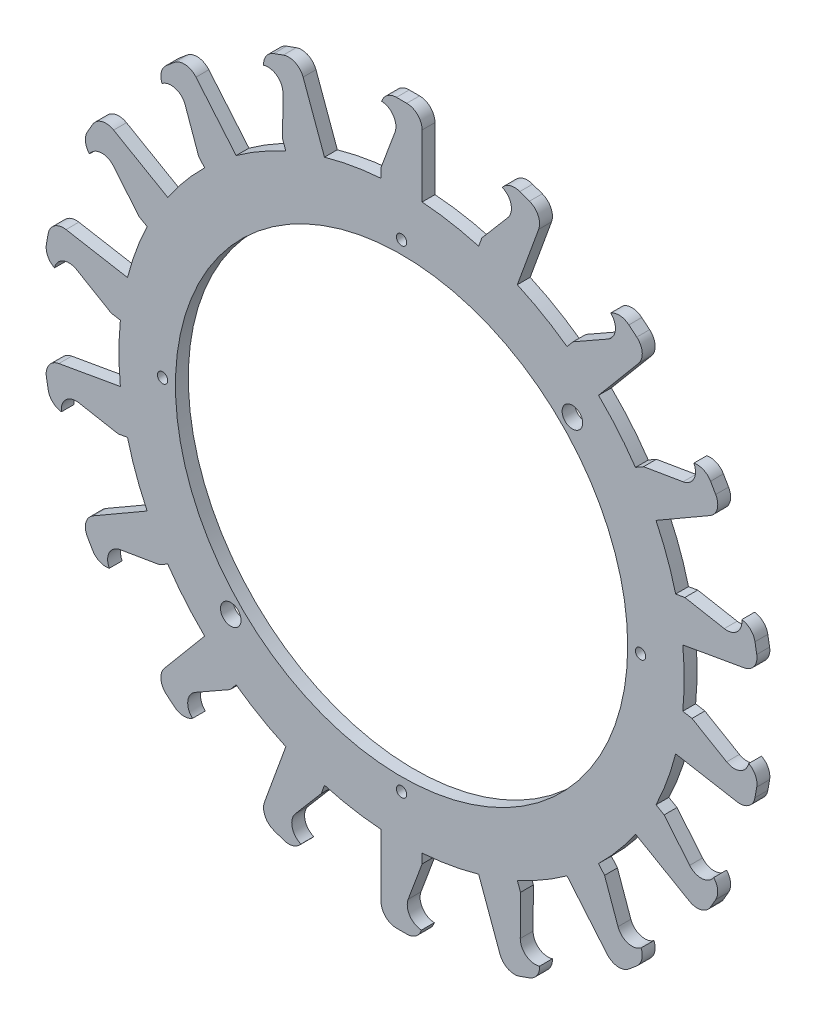
SolidWorks part; units mm, degrees
ref_plane "Front Plane" through (0, 0, 0) normal (0, 0, 1) x (1, 0, 0)
ref_plane "Top Plane" through (0, 0, 0) normal (0, 1, 0) x (1, 0, 0)
ref_plane "Right Plane" through (0, 0, 0) normal (1, 0, 0) x (0, 0, -1)
sketch "Sketch1" plane through (0, 0, 0) normal (0, 0, 1) x (1, 0, 0)
  line L0 (-78.3987, -3.3654) -> (61.3013, -3.3654) construction
  line L1 (-5.8227, 60.5836) -> (-5.8227, 59.1774)
  line L2 (-57.9401, 46.026) -> (40.8427, -52.7569) construction
  line L3 (40.8427, 46.026) -> (-57.9401, -52.7569) construction
  line L4 (-13.4427, 60.5073) -> (-13.4427, 59.1774)
  line L5 (-13.4427, 59.1774) -> (-5.8227, 59.1774)
  line L12 (2.7798, 58.212) -> (10.1401, 56.2398)
  line L13 (10.5041, 57.5981) -> (10.1401, 56.2398)
  line L14 (3.124, 59.4967) -> (2.7798, 58.212)
  line L18 (18.1997, 53.0809) -> (24.7988, 49.2709)
  line L19 (25.5019, 50.4887) -> (24.7988, 49.2709)
  line L20 (18.8647, 54.2327) -> (18.1997, 53.0809)
  line L24 (31.7661, 44.1336) -> (37.1543, 38.7454)
  line L25 (38.1486, 39.7398) -> (37.1543, 38.7454)
  line L26 (32.7065, 45.074) -> (31.7661, 44.1336)
  line L30 (42.5546, 31.9799) -> (46.3646, 25.3808)
  line L31 (47.5824, 26.0839) -> (46.3646, 25.3808)
  line L32 (43.7063, 32.6449) -> (42.5546, 31.9799)
  line L36 (49.8298, 17.4482) -> (51.802, 10.0878)
  line L37 (53.1603, 10.4518) -> (51.802, 10.0878)
  line L38 (51.1145, 17.7924) -> (49.8298, 17.4482)
  line L42 (53.0961, 1.5286) -> (53.0961, -6.0914)
  line L43 (54.5023, -6.0914) -> (53.0961, -6.0914)
  line L44 (54.426, 1.5286) -> (53.0961, 1.5286)
  line L48 (52.1307, -14.6939) -> (50.1585, -22.0543)
  line L49 (51.5168, -22.4183) -> (50.1585, -22.0543)
  line L50 (53.4154, -15.0382) -> (52.1307, -14.6939)
  line L54 (46.9996, -30.1138) -> (43.1896, -36.713)
  line L55 (44.4074, -37.4161) -> (43.1896, -36.713)
  line L56 (48.1513, -30.7788) -> (46.9996, -30.1138)
  line L60 (38.0523, -43.6803) -> (32.6641, -49.0684)
  line L61 (33.6585, -50.0628) -> (32.6641, -49.0684)
  line L62 (38.9927, -44.6207) -> (38.0523, -43.6803)
  line L66 (25.8986, -54.4687) -> (19.2995, -58.2787)
  line L67 (20.0026, -59.4965) -> (19.2995, -58.2787)
  line L68 (26.5636, -55.6205) -> (25.8986, -54.4687)
  line L72 (11.3669, -61.744) -> (4.0065, -63.7162)
  line L73 (4.3705, -65.0745) -> (4.0065, -63.7162)
  line L74 (11.7111, -63.0286) -> (11.3669, -61.744)
  line L78 (-4.5527, -65.0102) -> (-12.1727, -65.0102)
  line L79 (-12.1727, -66.4164) -> (-12.1727, -65.0102)
  line L80 (-4.5527, -66.3402) -> (-4.5527, -65.0102)
  line L84 (-20.7752, -64.0449) -> (-28.1356, -62.0727)
  line L85 (-28.4996, -63.431) -> (-28.1356, -62.0727)
  line L86 (-21.1195, -65.3295) -> (-20.7752, -64.0449)
  line L90 (-36.1951, -58.9137) -> (-42.7943, -55.1037)
  line L91 (-43.4974, -56.3215) -> (-42.7943, -55.1037)
  line L92 (-36.8601, -60.0655) -> (-36.1951, -58.9137)
  line L96 (-49.7616, -49.9665) -> (-55.1497, -44.5783)
  line L97 (-56.1441, -45.5726) -> (-55.1497, -44.5783)
  line L98 (-50.702, -50.9069) -> (-49.7616, -49.9665)
  line L102 (-60.55, -37.8128) -> (-64.36, -31.2137)
  line L103 (-65.5778, -31.9168) -> (-64.36, -31.2137)
  line L104 (-61.7018, -38.4778) -> (-60.55, -37.8128)
  line L109 (-71.1558, -16.2846) -> (-69.7975, -15.9207)
  line L110 (-69.1099, -23.6252) -> (-67.8253, -23.281)
  line L114 (-71.0915, -7.3614) -> (-71.0915, 0.2586)
  line L115 (-72.4977, 0.2586) -> (-71.0915, 0.2586)
  line L116 (-72.4215, -7.3614) -> (-71.0915, -7.3614)
  line L120 (-70.1262, 8.8611) -> (-68.154, 16.2214)
  line L121 (-69.5123, 16.5854) -> (-68.154, 16.2214)
  line L122 (-71.4108, 9.2053) -> (-70.1262, 8.8611)
  line L126 (-64.995, 24.281) -> (-61.185, 30.8801)
  line L127 (-62.4028, 31.5832) -> (-61.185, 30.8801)
  line L128 (-66.1468, 24.946) -> (-64.995, 24.281)
  line L132 (-56.0478, 37.8474) -> (-50.6596, 43.2356)
  line L133 (-51.6539, 44.2299) -> (-50.6596, 43.2356)
  line L134 (-56.9882, 38.7878) -> (-56.0478, 37.8474)
  line L138 (-43.8941, 48.6359) -> (-37.295, 52.4459)
  line L139 (-37.9981, 53.6637) -> (-37.295, 52.4459)
  line L140 (-44.5591, 49.7877) -> (-43.8941, 48.6359)
  line L144 (-29.3623, 55.9111) -> (-22.002, 57.8833)
  line L145 (-22.3659, 59.2416) -> (-22.002, 57.8833)
  line L146 (-29.7065, 57.1958) -> (-29.3623, 55.9111)
  line L147 (-8.9977, -2.9164) -> (-5.8227, 59.1774) construction
  line L148 (-8.9977, -2.9164) -> (10.1401, 56.2398) construction
  line L170 (-67.8253, -23.281) -> (-69.7975, -15.9207) [skipped]
  circle A0 centre (-8.5487, -3.3654) radius 55.88
  circle A1 centre (-8.5487, -3.3654) radius 69.85
  dimension "D1" = 111.76
  dimension "D2" = 139.7
  dimension "D4" = 7.62
  dimension "D5" = 24
  dimension "D6" = 15
extrude "Boss-Extrude1" add sketch "Sketch1" along normal blind 3.175
sketch "Sketch2" plane through (0, 0, 3.175) normal (0, 0, -1) x (-1, 0, 0)
  line L0 (8.5487, 66.4846) -> (8.5487, -73.2154) construction
  line L1 (8.5487, 62.6746) -> (13.6287, 62.6746)
  line L2 (8.5487, 62.6746) -> (3.4687, 62.6746)
  line L3 (3.4687, 62.6746) -> (3.4687, 85.5346)
  line L4 (3.4687, 85.5346) -> (13.6287, 85.5346)
  line L5 (13.6287, 85.5346) -> (13.6287, 62.6746)
  line L6 (8.5487, -3.3654) -> (-61.3013, -3.3654) construction
  line L7 (34.1807, 81.9107) -> (43.7279, 78.4358)
  line L8 (43.7279, 78.4358) -> (35.9094, 56.9544)
  line L9 (26.3621, 60.4293) -> (34.1807, 81.9107)
  line L10 (31.1357, 58.6919) -> (26.3621, 60.4293)
  line L11 (31.1357, 58.6919) -> (35.9094, 56.9544)
  line L12 (61.801, 68.0013) -> (69.584, 61.4705)
  line L13 (69.584, 61.4705) -> (54.8899, 43.9588)
  line L14 (47.1069, 50.4895) -> (61.801, 68.0013)
  line L15 (50.9984, 47.2241) -> (47.1069, 50.4895)
  line L16 (50.9984, 47.2241) -> (54.8899, 43.9588)
  line L17 (82.9984, 45.484) -> (88.0784, 36.6851)
  line L18 (88.0784, 36.6851) -> (68.281, 25.2551)
  line L19 (63.201, 34.054) -> (82.9984, 45.484)
  line L20 (65.741, 29.6546) -> (63.201, 34.054)
  line L21 (65.741, 29.6546) -> (68.281, 25.2551)
  line L22 (95.216, 17.0747) -> (96.9803, 7.0691)
  line L23 (96.9803, 7.0691) -> (74.4676, 3.0995)
  line L24 (72.7033, 13.1051) -> (95.216, 17.0747)
  line L25 (73.5854, 8.1023) -> (72.7033, 13.1051)
  line L26 (73.5854, 8.1023) -> (74.4676, 3.0995)
  line L27 (96.9803, -13.7999) -> (95.216, -23.8056)
  line L28 (95.216, -23.8056) -> (72.7033, -19.836)
  line L29 (74.4676, -9.8303) -> (96.9803, -13.7999)
  line L30 (73.5854, -14.8332) -> (74.4676, -9.8303)
  line L31 (73.5854, -14.8332) -> (72.7033, -19.836)
  line L32 (88.0784, -43.416) -> (82.9984, -52.2149)
  line L33 (82.9984, -52.2149) -> (63.201, -40.7849)
  line L34 (68.281, -31.986) -> (88.0784, -43.416)
  line L35 (65.741, -36.3854) -> (68.281, -31.986)
  line L36 (65.741, -36.3854) -> (63.201, -40.7849)
  line L37 (69.584, -68.2014) -> (61.801, -74.7322)
  line L38 (61.801, -74.7322) -> (47.1069, -57.2204)
  line L39 (54.8899, -50.6897) -> (69.584, -68.2014)
  line L40 (50.9984, -53.955) -> (54.8899, -50.6897)
  line L41 (50.9984, -53.955) -> (47.1069, -57.2204)
  line L42 (43.7279, -85.1667) -> (34.1807, -88.6416)
  line L43 (34.1807, -88.6416) -> (26.3621, -67.1602)
  line L44 (35.9094, -63.6853) -> (43.7279, -85.1667)
  line L45 (31.1357, -65.4227) -> (35.9094, -63.6853)
  line L46 (31.1357, -65.4227) -> (26.3621, -67.1602)
  line L47 (13.6287, -92.2654) -> (3.4687, -92.2654)
  line L48 (3.4687, -92.2654) -> (3.4687, -69.4054)
  line L49 (13.6287, -69.4054) -> (13.6287, -92.2654)
  line L50 (8.5487, -69.4054) -> (13.6287, -69.4054)
  line L51 (8.5487, -69.4054) -> (3.4687, -69.4054)
  line L52 (-17.0832, -88.6416) -> (-26.6305, -85.1667)
  line L53 (-26.6305, -85.1667) -> (-18.8119, -63.6853)
  line L54 (-9.2647, -67.1602) -> (-17.0832, -88.6416)
  line L55 (-14.0383, -65.4227) -> (-9.2647, -67.1602)
  line L56 (-14.0383, -65.4227) -> (-18.8119, -63.6853)
  line L57 (-44.7036, -74.7322) -> (-52.4866, -68.2014)
  line L58 (-52.4866, -68.2014) -> (-37.7925, -50.6897)
  line L59 (-30.0095, -57.2204) -> (-44.7036, -74.7322)
  line L60 (-33.901, -53.955) -> (-30.0095, -57.2204)
  line L61 (-33.901, -53.955) -> (-37.7925, -50.6897)
  line L62 (-65.9009, -52.2149) -> (-70.9809, -43.416)
  line L63 (-70.9809, -43.416) -> (-51.1836, -31.986)
  line L64 (-46.1036, -40.7849) -> (-65.9009, -52.2149)
  line L65 (-48.6436, -36.3854) -> (-46.1036, -40.7849)
  line L66 (-48.6436, -36.3854) -> (-51.1836, -31.986)
  line L67 (-78.1186, -23.8056) -> (-79.8828, -13.7999)
  line L68 (-79.8828, -13.7999) -> (-57.3701, -9.8303)
  line L69 (-55.6059, -19.836) -> (-78.1186, -23.8056)
  line L70 (-56.488, -14.8332) -> (-55.6059, -19.836)
  line L71 (-56.488, -14.8332) -> (-57.3701, -9.8303)
  line L72 (-79.8828, 7.0691) -> (-78.1186, 17.0747)
  line L73 (-78.1186, 17.0747) -> (-55.6059, 13.1051)
  line L74 (-57.3701, 3.0995) -> (-79.8828, 7.0691)
  line L75 (-56.488, 8.1023) -> (-57.3701, 3.0995)
  line L76 (-56.488, 8.1023) -> (-55.6059, 13.1051)
  line L77 (-70.9809, 36.6851) -> (-65.9009, 45.484)
  line L78 (-65.9009, 45.484) -> (-46.1036, 34.054)
  line L79 (-51.1836, 25.2551) -> (-70.9809, 36.6851)
  line L80 (-48.6436, 29.6546) -> (-51.1836, 25.2551)
  line L81 (-48.6436, 29.6546) -> (-46.1036, 34.054)
  line L82 (-52.4866, 61.4705) -> (-44.7036, 68.0013)
  line L83 (-44.7036, 68.0013) -> (-30.0095, 50.4895)
  line L84 (-37.7925, 43.9588) -> (-52.4866, 61.4705)
  line L85 (-33.901, 47.2241) -> (-37.7925, 43.9588)
  line L86 (-33.901, 47.2241) -> (-30.0095, 50.4895)
  line L87 (-26.6305, 78.4358) -> (-17.0832, 81.9107)
  line L88 (-17.0832, 81.9107) -> (-9.2647, 60.4293)
  line L89 (-18.8119, 56.9544) -> (-26.6305, 78.4358)
  line L90 (-14.0383, 58.6919) -> (-18.8119, 56.9544)
  line L91 (-14.0383, 58.6919) -> (-9.2647, 60.4293)
  circle A2 centre (8.5487, -3.3654) radius 69.85 construction
  point P99 (8.5487, -3.3654)
  dimension "D3" = 3.81
  dimension "D1" = 5.08
  dimension "D2" = 5.08
  dimension "D4" = 22.86
  dimension "D5" = 18
extrude "Boss-Extrude2" add sketch "Sketch2" along normal blind 3.175
fillet "Fillet4" radius 3.81 36 edges at (-13.6287, 85.5346, 1.5875) (-3.4687, 85.5346, 1.5875) (-88.0784, 36.6851, 1.5875) (-82.9984, 45.484, 1.5875) (-95.216, 17.0747, 1.5875) (-96.9803, 7.0691, 1.5875) (-96.9803, -13.7999, 1.5875) (-95.216, -23.8056, 1.5875) (-88.0784, -43.416, 1.5875) (-82.9984, -52.2149, 1.5875) (-69.584, -68.2014, 1.5875) (-61.801, -74.7322, 1.5875) (-43.7279, -85.1667, 1.5875) (-34.1807, -88.6416, 1.5875) (-13.6287, -92.2654, 1.5875) (-3.4687, -92.2654, 1.5875) (17.0832, -88.6416, 1.5875) (26.6305, -85.1667, 1.5875) (52.4866, -68.2014, 1.5875) (44.7036, -74.7322, 1.5875) (65.9009, -52.2149, 1.5875) (70.9809, -43.416, 1.5875) (78.1186, -23.8056, 1.5875) (79.8828, -13.7999, 1.5875) (79.8828, 7.0691, 1.5875) (78.1186, 17.0747, 1.5875) (70.9809, 36.6851, 1.5875) (65.9009, 45.484, 1.5875) (52.4866, 61.4705, 1.5875) (44.7036, 68.0013, 1.5875) (26.6305, 78.4358, 1.5875) (17.0832, 81.9107, 1.5875) (-69.584, 61.4705, 1.5875) (-61.801, 68.0013, 1.5875) (-43.7279, 78.4358, 1.5875) (-34.1807, 81.9107, 1.5875)
sketch "Sketch3" plane through (0, 0, 0) normal (0, 0, -1) x (-1, 0, 0)
  line L0 (17.0808, 69.8995) -> (13.6287, 79.1846) construction
  line L1 (13.6287, 66.2996) -> (13.6287, 81.7246) construction
  line L2 (13.6287, 68.616) -> (10.1766, 77.9011)
  line L3 (20.533, 71.183) -> (17.0808, 80.468)
  line L4 (13.6287, 66.2996) -> (13.6287, 81.7246) construction
  line L5 (8.5487, 52.5146) -> (8.5487, -59.2454) construction
  line L6 (-47.3313, -3.3654) -> (64.4287, -3.3654) construction
  line L7 (41.6244, 62.563) -> (41.5561, 72.4687) construction
  line L8 (37.9415, 62.5376) -> (37.8732, 72.4433)
  line L9 (45.3073, 62.5883) -> (45.239, 72.4941)
  line L10 (62.1785, 47.2744) -> (65.5023, 56.6062) construction
  line L11 (58.709, 48.5102) -> (62.0329, 57.8419)
  line L12 (65.648, 46.0387) -> (68.9718, 55.3704)
  line L13 (76.2641, 25.878) -> (82.5791, 33.5101) construction
  line L14 (73.4265, 28.2259) -> (79.7415, 35.858)
  line L15 (79.1017, 23.5301) -> (85.4167, 31.1623)
  line L16 (82.1822, 0.9544) -> (90.7267, 5.9664) construction
  line L17 (80.3188, 4.1312) -> (88.8633, 9.1432)
  line L18 (84.0457, -2.2224) -> (92.5902, 2.7896)
  line L19 (79.219, -24.4903) -> (88.9625, -22.7029) construction
  line L20 (78.5545, -20.8677) -> (88.2979, -19.0804)
  line L21 (79.8836, -28.1128) -> (89.627, -26.3255)
  line L22 (67.732, -47.387) -> (77.4991, -49.0399) construction
  line L23 (68.3465, -43.7556) -> (78.1137, -45.4085)
  line L24 (67.1175, -51.0183) -> (76.8846, -52.6712)
  line L25 (49.1066, -64.974) -> (57.7193, -69.8678) construction
  line L26 (50.926, -61.7718) -> (59.5388, -66.6656)
  line L27 (47.2871, -68.1762) -> (55.8999, -73.07)
  line L28 (25.5892, -75.1302) -> (32.0088, -82.6745) construction
  line L29 (28.3942, -72.7434) -> (34.8138, -80.2878)
  line L30 (22.7843, -77.5169) -> (29.2039, -85.0613)
  line L31 (0.0166, -76.6304) -> (3.4687, -85.9154) construction
  line L32 (3.4687, -75.3469) -> (6.9208, -84.632)
  line L33 (-3.4355, -77.9139) -> (0.0166, -87.1989)
  line L34 (-24.527, -69.2938) -> (-24.4587, -79.1996) construction
  line L35 (-20.844, -69.2685) -> (-20.7758, -79.1742)
  line L36 (-28.2099, -69.3192) -> (-28.1416, -79.225)
  line L37 (-45.0811, -54.0053) -> (-48.4049, -63.3371) construction
  line L38 (-41.6116, -55.2411) -> (-44.9354, -64.5728)
  line L39 (-48.5506, -52.7695) -> (-51.8744, -62.1013)
  line L40 (-59.1667, -32.6089) -> (-65.4817, -40.241) construction
  line L41 (-56.3291, -34.9568) -> (-62.6441, -42.5889)
  line L42 (-62.0043, -30.261) -> (-68.3193, -37.8931)
  line L43 (-65.0848, -7.6853) -> (-73.6293, -12.6973) construction
  line L44 (-63.2213, -10.8621) -> (-71.7659, -15.8741)
  line L45 (-66.9482, -4.5085) -> (-75.4927, -9.5205)
  line L46 (-62.1216, 17.7594) -> (-71.865, 15.972) construction
  line L47 (-61.4571, 14.1368) -> (-71.2005, 12.3495)
  line L48 (-62.7861, 21.3819) -> (-72.5296, 19.5946)
  line L49 (-50.6345, 40.6561) -> (-60.4017, 42.309) construction
  line L50 (-51.2491, 37.0247) -> (-61.0162, 38.6776)
  line L51 (-50.02, 44.2874) -> (-59.7871, 45.9403)
  line L52 (-32.0091, 58.2431) -> (-40.6219, 63.1369) construction
  line L53 (-33.8286, 55.0409) -> (-42.4414, 59.9347)
  line L54 (-30.1896, 61.4453) -> (-38.8024, 66.3391)
  line L55 (-8.4918, 68.3993) -> (-14.9114, 75.9436) construction
  line L56 (-11.2968, 66.0125) -> (-17.7164, 73.5569)
  line L57 (-5.6868, 70.786) -> (-12.1064, 78.3304)
  line L58 (8.5487, -3.3654) -> (17.0808, 69.8995) construction
  arc A0 (13.6287, 68.616) -> (20.533, 71.183) centre (17.0808, 69.8995) ccw
  arc A1 (17.0808, 80.468) -> (10.1766, 77.9011) centre (13.6287, 79.1846) ccw
  circle A2 centre (8.5487, -3.3654) radius 55.88 construction
  arc A3 (37.9415, 62.5376) -> (45.3073, 62.5883) centre (41.6244, 62.563) ccw
  arc A4 (45.239, 72.4941) -> (37.8732, 72.4433) centre (41.5561, 72.4687) ccw
  arc A5 (58.709, 48.5102) -> (65.648, 46.0387) centre (62.1785, 47.2744) ccw
  arc A6 (68.9718, 55.3704) -> (62.0329, 57.8419) centre (65.5023, 56.6062) ccw
  arc A7 (73.4265, 28.2259) -> (79.1017, 23.5301) centre (76.2641, 25.878) ccw
  arc A8 (85.4167, 31.1623) -> (79.7415, 35.858) centre (82.5791, 33.5101) ccw
  arc A9 (80.3188, 4.1312) -> (84.0457, -2.2224) centre (82.1822, 0.9544) ccw
  arc A10 (92.5902, 2.7896) -> (88.8633, 9.1432) centre (90.7267, 5.9664) ccw
  arc A11 (78.5545, -20.8677) -> (79.8836, -28.1128) centre (79.219, -24.4903) ccw
  arc A12 (89.627, -26.3255) -> (88.2979, -19.0804) centre (88.9625, -22.7029) ccw
  arc A13 (68.3465, -43.7556) -> (67.1175, -51.0183) centre (67.732, -47.387) ccw
  arc A14 (76.8846, -52.6712) -> (78.1137, -45.4085) centre (77.4991, -49.0399) ccw
  arc A15 (50.926, -61.7718) -> (47.2871, -68.1762) centre (49.1066, -64.974) ccw
  arc A16 (55.8999, -73.07) -> (59.5388, -66.6656) centre (57.7193, -69.8678) ccw
  arc A17 (28.3942, -72.7434) -> (22.7843, -77.5169) centre (25.5892, -75.1302) ccw
  arc A18 (29.2039, -85.0613) -> (34.8138, -80.2878) centre (32.0088, -82.6745) ccw
  arc A19 (3.4687, -75.3469) -> (-3.4355, -77.9139) centre (0.0166, -76.6304) ccw
  arc A20 (0.0166, -87.1989) -> (6.9208, -84.632) centre (3.4687, -85.9154) ccw
  arc A21 (-20.844, -69.2685) -> (-28.2099, -69.3192) centre (-24.527, -69.2938) ccw
  arc A22 (-28.1416, -79.225) -> (-20.7758, -79.1742) centre (-24.4587, -79.1996) ccw
  arc A23 (-41.6116, -55.2411) -> (-48.5506, -52.7695) centre (-45.0811, -54.0053) ccw
  arc A24 (-51.8744, -62.1013) -> (-44.9354, -64.5728) centre (-48.4049, -63.3371) ccw
  arc A25 (-56.3291, -34.9568) -> (-62.0043, -30.261) centre (-59.1667, -32.6089) ccw
  arc A26 (-68.3193, -37.8931) -> (-62.6441, -42.5889) centre (-65.4817, -40.241) ccw
  arc A27 (-63.2213, -10.8621) -> (-66.9482, -4.5085) centre (-65.0848, -7.6853) ccw
  arc A28 (-75.4927, -9.5205) -> (-71.7659, -15.8741) centre (-73.6293, -12.6973) ccw
  arc A29 (-61.4571, 14.1368) -> (-62.7861, 21.3819) centre (-62.1216, 17.7594) ccw
  arc A30 (-72.5296, 19.5946) -> (-71.2005, 12.3495) centre (-71.865, 15.972) ccw
  arc A31 (-51.2491, 37.0247) -> (-50.02, 44.2874) centre (-50.6345, 40.6561) ccw
  arc A32 (-59.7871, 45.9403) -> (-61.0162, 38.6776) centre (-60.4017, 42.309) ccw
  arc A33 (-33.8286, 55.0409) -> (-30.1896, 61.4453) centre (-32.0091, 58.2431) ccw
  arc A34 (-38.8024, 66.3391) -> (-42.4414, 59.9347) centre (-40.6219, 63.1369) ccw
  arc A35 (-11.2968, 66.0125) -> (-5.6868, 70.786) centre (-8.4918, 68.3993) ccw
  arc A36 (-12.1064, 78.3304) -> (-17.7164, 73.5569) centre (-14.9114, 75.9436) ccw
  point P4 (15.3548, 74.542)
  point P10 (9.1837, -3.8983)
  point P11 (9.1837, -3.8983)
  point P21 (41.5903, 67.5158)
  point P28 (63.8404, 51.9403)
  point P35 (79.4216, 29.6941)
  point P42 (86.4545, 3.4604)
  point P49 (84.0908, -23.5966)
  point P56 (72.6156, -48.2134)
  point P63 (53.4129, -67.4209)
  point P70 (28.799, -78.9023)
  point P77 (1.7427, -81.2729)
  point P84 (-24.4928, -74.2467)
  point P91 (-46.743, -58.6712)
  point P98 (-62.3242, -36.425)
  point P105 (-69.357, -10.1913)
  point P112 (-66.9933, 16.8657)
  point P119 (-55.5181, 41.4825)
  point P126 (-36.3155, 60.69)
  point P131 (9.1837, -3.8983)
  point P133 (9.1837, -3.8983)
  point P134 (9.1837, -3.8983)
  point P135 (9.1837, -3.8983)
  point P136 (9.1837, -3.8983)
  point P137 (9.1837, -3.8983)
  point P138 (9.1837, -3.8983)
  point P139 (9.1837, -3.8983)
  point P140 (9.1837, -3.8983)
  point P141 (9.1837, -3.8983)
  point P142 (9.1837, -3.8983)
  point P143 (9.1837, -3.8983)
  point P144 (9.1837, -3.8983)
  point P145 (9.1837, -3.8983)
  point P146 (9.1837, -3.8983)
  point P152 (-11.7016, 72.1715)
  dimension "D1" = 7.366
  dimension "D2" = 6.35
  dimension "D3" = 9.906
  dimension "D4" = 18
  dimension "D5" = 73.7601
extrude "Cut-Extrude1" cut sketch "Sketch3" against normal through all
sketch "Sketch4" plane through (0, 0, 0) normal (0, 0, -1) x (-1, 0, 0)
  line L0 (8.5487, 52.5146) -> (8.5487, -59.2454) construction
  line L1 (-47.3313, -3.3654) -> (64.4287, -3.3654) construction
  line L2 (8.5487, -3.3654) -> (81.6471, -76.4638) construction
  line L3 (8.5487, -3.3654) -> (-56.7065, 61.8898) construction
  circle A0 centre (8.5487, -3.3654) radius 55.88 construction
  circle A1 centre (8.5487, -3.3654) radius 59.055
  circle A2 centre (8.5487, 55.6896) radius 1.27
  circle A3 centre (8.5487, -62.4204) radius 1.27
  circle A4 centre (-50.5063, -3.3654) radius 1.27
  circle A5 centre (67.6037, -3.3654) radius 1.27
  circle A6 centre (8.5487, -3.3654) radius 62.23
  circle A7 centre (-33.6585, 38.8418) radius 2.54
  circle A8 centre (50.7559, -45.5726) radius 2.54
  dimension "D1" = 118.11
  dimension "D2" = 2.54
  dimension "D3" = 2.54
  dimension "D4" = 2.54
  dimension "D5" = 2.54
  dimension "D8" = 124.46
  dimension "D9" = 5.08
  dimension "D10" = 5.08
  dimension "D6" = 45
  dimension "D7" = 45
extrude "Cut-Extrude2" cut sketch "Sketch4" against normal through all contours A1 A2 | A1 A2 | A1 A4 | A1 A4 | A1 A3 | A1 A3 | A1 A5 | A1 A5 | A1 A7 | A1 A7 | A1 A8 | A1 A8
